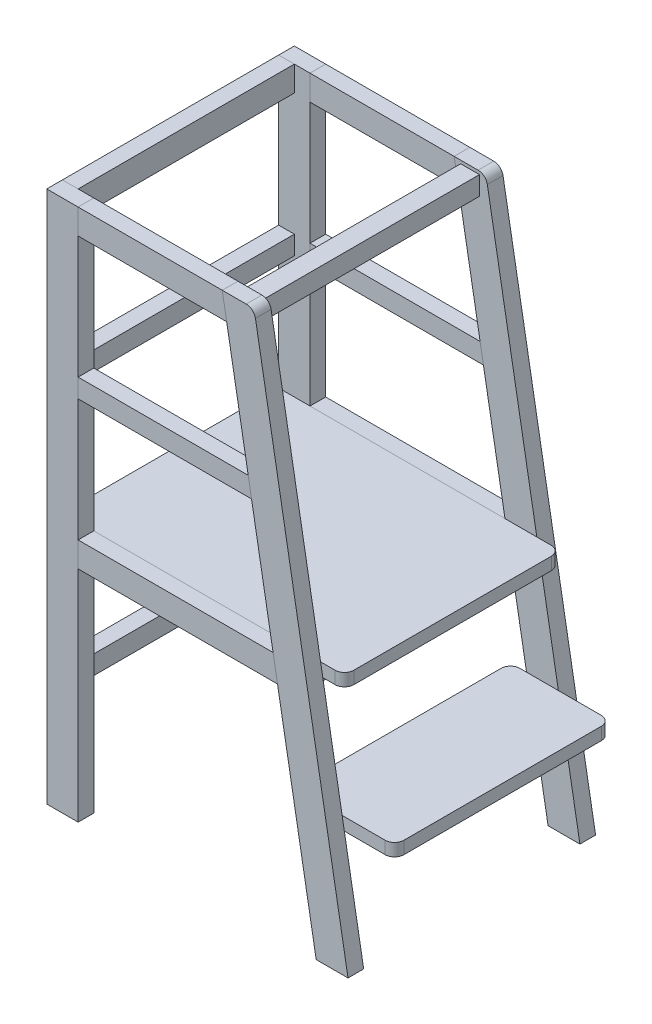
SolidWorks part; units mm, degrees
ref_plane "Plan de face" through (0, 0, 0) normal (0, 0, 1) x (1, 0, 0)
ref_plane "Plan de dessus" through (0, 0, 0) normal (0, 1, 0) x (1, 0, 0)
ref_plane "Plan de droite" through (0, 0, 0) normal (1, 0, 0) x (0, 0, -1)
sketch "Esquisse1" plane through (0, 0, 0) normal (0, 0, 1) x (1, 0, 0)
  line L0 (0, 0) -> (50, 0)
  line L1 (50, 0) -> (50, 850)
  line L2 (50, 850) -> (0, 850)
  line L3 (0, 850) -> (0, 0)
  line L8 (330.7713, 850) -> (280, 850)
  line L9 (280, 850) -> (429.8779, 0)
  line L10 (429.8779, 0) -> (480.6493, 0)
  line L11 (480.6493, 0) -> (330.7713, 850)
  line L12 (280, 850) -> (280, 110.6616) construction
  dimension "D1" = 50
  dimension "D2" = 850
  dimension "D3" = 50
  dimension "D4" = 280
  dimension "D5" = 10
extrude "Boss.-Extru.1" add sketch "Esquisse1" along normal blind 25
sketch "Esquisse2" plane through (0, 0, 25) normal (0, 0, 1) x (1, 0, 0)
  line L0 (280, 850) -> (50, 850)
  line L1 (50, 850) -> (50, 810)
  line L2 (50, 0) -> (50, 850) construction
  line L3 (50, 810) -> (287.0531, 810)
  line L4 (280, 850) -> (429.8779, 0) construction
  line L5 (287.0531, 810) -> (280, 850)
  line L6 (50, 390) -> (50, 350)
  line L7 (50, 350) -> (368.1635, 350)
  line L8 (368.1635, 350) -> (361.1104, 390)
  line L9 (361.1104, 390) -> (50, 390)
  line L10 (0, 0) -> (50, 0) construction
  line L11 (50, 615) -> (50, 585)
  line L12 (50, 585) -> (326.7266, 585)
  line L13 (326.7266, 585) -> (321.4368, 615)
  line L14 (321.4368, 615) -> (50, 615)
  line L15 (188.3633, 585) -> (188.3633, 390) construction
  line L16 (185.7184, 615) -> (185.7184, 810) construction
  dimension "D1" = 40
  dimension "D2" = 350
  dimension "D3" = 30
extrude "Boss.-Extru.2" add sketch "Esquisse2" against normal up to vertex (25 mm away) separate body up to point (280, 850, 0)
pattern_linear "Répétition linéaire1" count 2 spacing 370 along (0, 0, -1) of "Boss.-Extru.1", "Boss.-Extru.2"
sketch "Esquisse4" plane through (0, 0, 0) normal (-1, 0, 0) x (0, 0, 1)
  line L0 (-345, 850) -> (-345, 0) construction
  line L1 (-345, 195) -> (0, 195)
  line L2 (-345, 195) -> (-345, 165)
  line L3 (-345, 165) -> (0, 165)
  line L4 (0, 195) -> (0, 165)
  line L5 (0, 850) -> (0, 0) construction
  line L7 (-345, 850) -> (0, 850)
  line L8 (-345, 850) -> (-345, 810)
  line L9 (-345, 810) -> (0, 810)
  line L10 (0, 850) -> (0, 810)
  dimension "D1" = 30
  dimension "D2" = 165
  dimension "D3" = 40
extrude "Boss.-Extru.3" add sketch "Esquisse4" against normal blind 25 separate body
sketch "Esquisse5" plane through (0, 850, 0) normal (0, 1, 0) x (1, 0, 0)
  line L0 (330.7713, 0) -> (280, 0) construction
  line L1 (320.3857, 0) -> (290.3857, 0)
  line L2 (320.3857, 0) -> (320.3857, 345)
  line L3 (320.3857, 345) -> (290.3857, 345)
  line L4 (290.3857, 0) -> (290.3857, 345)
  line L5 (330.7713, 345) -> (280, 345) construction
  line L6 (305.3857, 345) -> (305.3857, 0) construction
  dimension "D1" = 30
extrude "Boss.-Extru.4" add sketch "Esquisse5" against normal blind 30 from offset 5 separate body offset against normal yes
fillet "Congé2" radius 15 1 edges at (330.7713, 850, -357.5)
fillet "Congé3" radius 15 1 edges at (330.7713, 850, 12.5)
sketch "Esquisse6" plane through (0, 0, 25) normal (0, 0, 1) x (1, 0, 0)
  line L0 (429.8779, 0) -> (480.6493, 0) construction
  line L1 (369.8779, 195) -> (529.8779, 195)
  line L2 (369.8779, 195) -> (369.8779, 175)
  line L3 (369.8779, 175) -> (529.8779, 175)
  line L4 (529.8779, 195) -> (529.8779, 175)
  dimension "D1" = 160
  dimension "D2" = 175
  dimension "D3" = 60
  dimension "D4" = 20
extrude "Boss.-Extru.6" add sketch "Esquisse6" against normal up to vertex (370 mm away) from surface at -25 separate body starting at face at (368.7849, 508.0586, 0)
fillet "Congé5" radius 15 4 edges at (369.8779, 185, -345) (369.8779, 185, 0) (529.8779, 185, -345) (529.8779, 185, 0)
sketch "Esquisse7" plane through (0, 0, 0) normal (-1, 0, 0) x (0, 0, 1)
  line L0 (-345, 850) -> (-345, 0) construction
  line L1 (-345, 390) -> (0, 390)
  line L2 (-345, 390) -> (-345, 370)
  line L3 (-345, 370) -> (0, 370)
  line L4 (0, 390) -> (0, 370)
  line L5 (0, 850) -> (0, 0) construction
  dimension "D1" = 20
  dimension "D2" = 370
extrude "Boss.-Extru.9" add sketch "Esquisse7" against normal blind 450 separate body
fillet "Congé6" radius 15 2 edges at (450, 380, -345) (450, 380, 0)
sketch "Esquisse9" plane through (0, 0, 0) normal (-1, 0, 0) x (0, 0, 1)
  line L0 (-345, 850) -> (-345, 0) construction
  line L1 (-345, 585) -> (0, 585)
  line L2 (-345, 585) -> (-345, 615)
  line L3 (-345, 615) -> (0, 615)
  line L4 (0, 585) -> (0, 615)
  line L5 (0, 850) -> (0, 0) construction
  line L6 (0, 615) -> (25, 615) construction
  line L7 (0, 585) -> (25, 585) construction
extrude "Boss.-Extru.11" add sketch "Esquisse9" against normal blind 25 separate body
